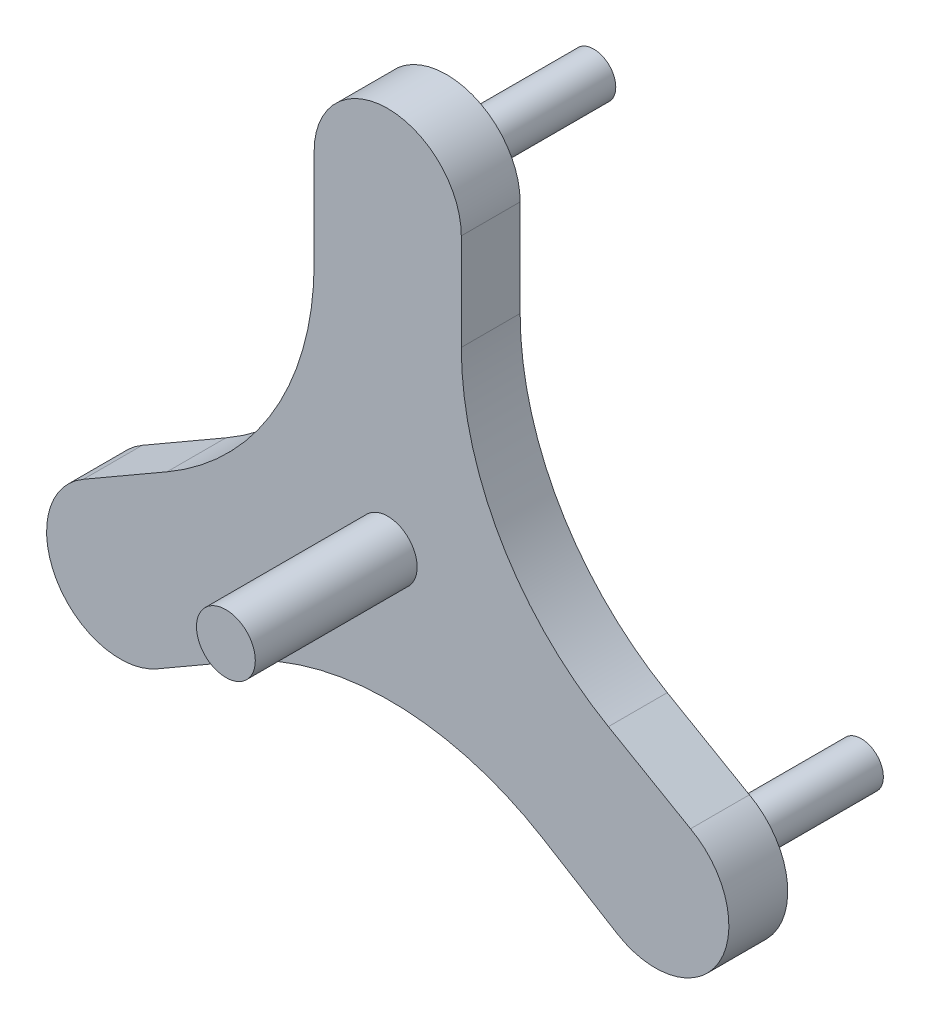
SolidWorks part; units mm, degrees
ref_plane "Front" through (0, 0, 0) normal (0, 0, 1) x (1, 0, 0)
ref_plane "Top" through (0, 0, 0) normal (0, 1, 0) x (1, 0, 0)
ref_plane "Right" through (0, 0, 0) normal (1, 0, 0) x (0, 0, -1)
sketch "Эскиз1" plane through (0, 0, 0) normal (0, 0, 1) x (1, 0, 0)
  line L3 (-1.3027, -2.1346) -> (-3.8095, -0.6048)
  line L4 (1.1973, 2.1955) -> (-1.5933, 3.8066)
  line L5 (-19.4365, 2.1651) -> (-16.5933, 3.8066)
  line L6 (-16.9365, -2.1651) -> (-14.0188, -0.4805)
  line L7 (-6.5933, 15.75) -> (-6.5933, 12.4669)
  line L8 (-11.5933, 15.75) -> (-11.5933, 12.4669)
  arc A0 (-1.3027, -2.1346) -> (1.1973, 2.1955) centre (0, 0) ccw
  arc A1 (-19.4365, 2.1651) -> (-16.9365, -2.1651) centre (-18.1865, 0) ccw
  arc A2 (-6.5933, 15.75) -> (-11.5933, 15.75) centre (-9.0933, 15.75) ccw
  arc A3 (-3.8095, -0.6048) -> (-14.0188, -0.4805) centre (-9.0188, -9.1408) ccw
  arc A4 (-1.5933, 3.8066) -> (-6.5933, 12.4669) centre (3.4067, 12.4669) cw
  arc A5 (-16.5933, 3.8066) -> (-11.5933, 12.4669) centre (-21.5933, 12.4669) ccw
  point P13 (-9.0933, 5.25)
  point P25 (-9.0933, 5.25)
  dimension "D4" = 10
  dimension "D5" = 10
  dimension "D3" = 10
extrude "Бобышка-Вытянуть1" add sketch "Эскиз1" along normal blind 2
sketch "Эскиз2" plane through (0, 0, 0) normal (0, 0, -1) x (-1, 0, 0)
  circle A0 centre (9.0933, 5.25) radius 10.5 construction
  circle A1 centre (0, 0) radius 0.75
  circle A2 centre (9.0933, 15.75) radius 0.75
  circle A3 centre (18.1865, 0) radius 0.75
  point P12 (9.0933, 5.25)
  dimension "D1" = 1.5
  dimension "D2" = 3
extrude "Бобышка-Вытянуть2" add sketch "Эскиз2" along normal blind 5
sketch "Эскиз4" plane through (0, 0, 2) normal (0, 0, 1) x (1, 0, 0)
  circle A0 centre (-9.0933, 5.25) radius 1
  dimension "D1" = 2
extrude "Бобышка-Вытянуть3" add sketch "Эскиз4" along normal blind 5.5
